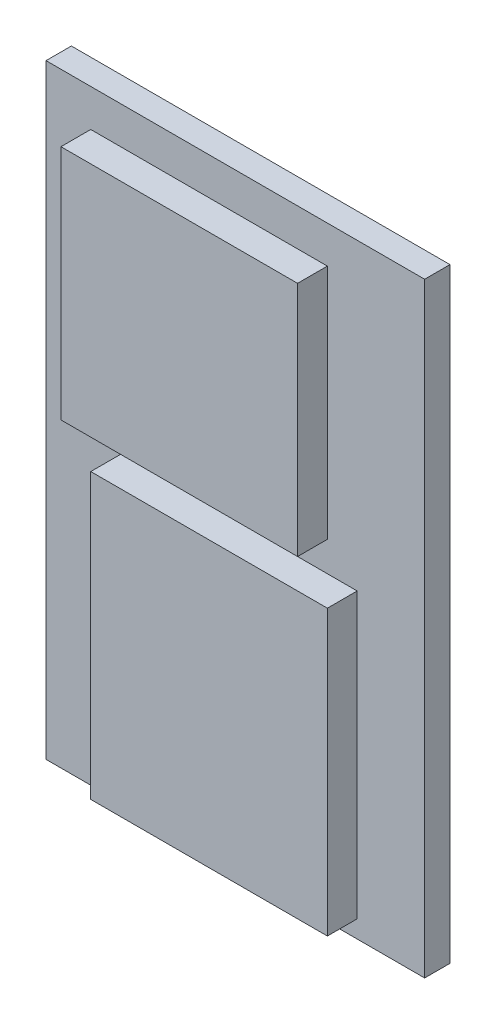
SolidWorks part; units mm, degrees
ref_plane "Front Plane" through (0, 0, 0) normal (0, 0, 1) x (1, 0, 0)
ref_plane "Top Plane" through (0, 0, 0) normal (0, 1, 0) x (1, 0, 0)
ref_plane "Right Plane" through (0, 0, 0) normal (1, 0, 0) x (0, 0, -1)
sketch "Sketch1" plane through (0, 0, 0) normal (0, 0, 1) x (1, 0, 0)
  line L1 (-12.7, -20.3) -> (12.7, -20.3)
  line L2 (-12.7, -20.3) -> (-12.7, 20.3)
  line L3 (-12.7, 20.3) -> (12.7, 20.3)
  line L4 (12.7, -20.3) -> (12.7, 20.3)
  line L5 (-12.7, -20.3) -> (12.7, 20.3) construction
  line L6 (-12.7, 20.3) -> (12.7, -20.3) construction
  point P0 (0, 0)
  dimension "D1" = 25.4
  dimension "D2" = 40.6
extrude "Boss-Extrude1" add sketch "Sketch1" along normal blind 1.7
sketch "Sketch2" plane through (0, 0, 0) normal (0, 0, 1) x (1, 0, 0)
  line L0 (-12.7, -20.3) -> (12.7, -20.3) construction
  line L3 (-4, -13.3) -> (4, -13.3)
  line L5 (-4, -20.3) -> (4, -20.3)
  line L7 (-4, -20.3) -> (-4, -13.3)
  line L8 (4, -13.3) -> (4, -20.3)
  line L9 (12.7, -20.3) -> (12.7, 20.3) construction
  dimension "D1" = 8
  dimension "D2" = 7
extrude "Boss-Extrude2" add sketch "Sketch2" against normal blind 2.5
sketch "Sketch3" plane through (0, -20.3, 0) normal (0, -1, 0) x (1, 0, 0)
  line L0 (3.5, -2.125) -> (3.5, -1.125)
  line L1 (3.5, -1.125) -> (2.375, 0)
  line L2 (2.375, 0) -> (-2.375, 0)
  line L3 (-2.375, 0) -> (-3.5, -1.125)
  line L4 (-3.5, -1.125) -> (-3.5, -2.125)
  line L5 (-3.5, -2.125) -> (3.5, -2.125)
  line L6 (0, 0) -> (0, -3.7266) construction
  point P2 (0, 0)
  point P10 (0, 0)
  dimension "D1" = 4.75
  dimension "D2" = 7
  dimension "D4" = 1
extrude "Cut-Extrude2" cut sketch "Sketch3" against normal blind 5
fillet "Fillet1" radius 1 2 edges at (-4, -16.8, -2.5) (4, -16.8, -2.5)
fillet "Fillet2" radius 1 2 edges at (-4, -16.8, 0) (4, -16.8, 0)
sketch "Sketch4" plane through (0, 0, 0) normal (0, 0, -1) x (-1, 0, 0)
  line L1 (-9.4, -9.6) -> (9.4, -9.6)
  line L2 (-9.4, -9.6) -> (-9.4, 9.6)
  line L3 (-9.4, 9.6) -> (9.4, 9.6)
  line L4 (9.4, -9.6) -> (9.4, 9.6)
  line L5 (-9.4, -9.6) -> (9.4, 9.6) construction
  line L6 (-9.4, 9.6) -> (9.4, -9.6) construction
  point P0 (0, 0)
  dimension "D1" = 18.8
  dimension "D2" = 19.2
extrude "Boss-Extrude3" add sketch "Sketch4" along normal blind 2.5
sketch "Sketch5" plane through (0, 0, 0) normal (0, 0, -1) x (-1, 0, 0)
  line L0 (-5, -20.3) -> (-12.7, -20.3) construction
  line L1 (-12.7, -20.3) -> (-12.7, 20.3) construction
  circle A0 centre (-8.2, -17.8) radius 1.75
  dimension "D1" = 3.5
  dimension "D2" = 2.5
  dimension "D3" = 4.5
extrude "Boss-Extrude4" add sketch "Sketch5" along normal blind 2
sketch "Sketch6" plane through (0, 0, 0) normal (0, 0, -1) x (-1, 0, 0)
  line L0 (-9.4, -9.6) -> (9.4, -9.6) construction
  line L1 (-6.95, -10.6) -> (-7.45, -10.6)
  line L2 (-6.95, -10.6) -> (-6.95, -11.6)
  line L3 (-6.95, -11.6) -> (-7.45, -11.6)
  line L4 (-7.45, -10.6) -> (-7.45, -11.6)
  line L5 (-6.95, -10.6) -> (-7.45, -11.6) construction
  line L6 (-6.95, -11.6) -> (-7.45, -10.6) construction
  line L7 (-12.7, -20.3) -> (-12.7, 20.3) construction
  line L8 (-6.2, -10.6) -> (-6.7, -10.6)
  line L9 (-6.2, -10.6) -> (-6.2, -11.6)
  line L10 (-6.2, -11.6) -> (-6.7, -11.6)
  line L11 (-6.7, -10.6) -> (-6.7, -11.6)
  line L12 (-6.2, -10.6) -> (-6.7, -11.6) construction
  line L13 (-6.2, -11.6) -> (-6.7, -10.6) construction
  point P0 (-7.2, -11.1)
  point P9 (-6.45, -11.1)
  point P14 (0, 0)
  dimension "D1" = 1.5
  dimension "D2" = 0.5
  dimension "D3" = 1
  dimension "D4" = 5.5
  dimension "D5" = 0.25
extrude "Boss-Extrude5" add sketch "Sketch6" along normal blind 0.5
sketch "Sketch7" plane through (0, 0, 0) normal (0, 0, -1) x (-1, 0, 0)
  line L0 (-12.7, 20.3) -> (12.7, 20.3) construction
  line L1 (-10.2, 17.8) -> (-8.2, 17.8)
  line L2 (-10.2, 17.8) -> (-10.2, 14.8)
  line L3 (-10.2, 14.8) -> (-8.2, 14.8)
  line L4 (-8.2, 17.8) -> (-8.2, 14.8)
  line L5 (-10.2, 17.8) -> (-8.2, 14.8) construction
  line L6 (-10.2, 14.8) -> (-8.2, 17.8) construction
  line L7 (-12.7, -20.3) -> (-12.7, 20.3) construction
  line L8 (8.2, 17.8) -> (10.2, 17.8)
  line L9 (8.2, 17.8) -> (8.2, 14.8)
  line L10 (8.2, 14.8) -> (10.2, 14.8)
  line L11 (10.2, 17.8) -> (10.2, 14.8)
  line L12 (8.2, 17.8) -> (10.2, 14.8) construction
  line L13 (8.2, 14.8) -> (10.2, 17.8) construction
  line L14 (12.7, 20.3) -> (12.7, -20.3) construction
  point P0 (-9.2, 16.3)
  point P9 (9.2, 16.3)
  point P14 (5.4266, 15.915)
  dimension "D1" = 2.5
  dimension "D2" = 2.5
  dimension "D3" = 2
  dimension "D4" = 3
  dimension "D5" = 2.5
extrude "Boss-Extrude6" add sketch "Sketch7" along normal blind 2
sketch "Sketch8" plane through (0, 0, 1.7) normal (0, 0, 1) x (1, 0, 0)
  line L0 (-10.2, 17.8) -> (11.0962, 17.8) construction
  line L1 (-10.2, 17.8) -> (-10.2, 7.4618) construction
  line L2 (-12.7, 20.3) -> (-12.7, -20.3) construction
  line L3 (12.7, 20.3) -> (-12.7, 20.3) construction
  line L5 (6.175, 1.925) -> (-9.7, 1.925)
  line L6 (6.175, 1.925) -> (6.175, 17.8)
  line L7 (6.175, 17.8) -> (-9.7, 17.8)
  line L8 (-9.7, 1.925) -> (-9.7, 17.8)
  line L9 (6.175, 1.925) -> (-9.7, 17.8) construction
  line L10 (6.175, 17.8) -> (-9.7, 1.925) construction
  line L11 (-7.7, -0.075) -> (8.175, -0.075)
  line L12 (-7.7, -0.075) -> (-7.7, -19.125)
  line L13 (-7.7, -19.125) -> (8.175, -19.125)
  line L14 (8.175, -0.075) -> (8.175, -19.125)
  line L15 (-7.7, -0.075) -> (8.175, -19.125) construction
  line L16 (-7.7, -19.125) -> (8.175, -0.075) construction
  point P7 (-1.7625, 9.8625)
  point P12 (0.2375, -9.6)
  point P17 (-0.4357, -9.9128)
  point P18 (2.1786, -8.6601)
  dimension "D1" = 2.5
  dimension "D2" = 2.5
  dimension "D3" = 1
  dimension "D4" = 15.875
  dimension "D5" = 15.875
  dimension "D6" = 15.875
  dimension "D7" = 19.05
  dimension "D8" = 2
  dimension "D9" = 2
extrude "Boss-Extrude7" add sketch "Sketch8" along normal blind 2
equation "\"D5@Sketch8\"=\"D4@Sketch8\""
equation "\"D6@Sketch8\"=\"D4@Sketch8\""
